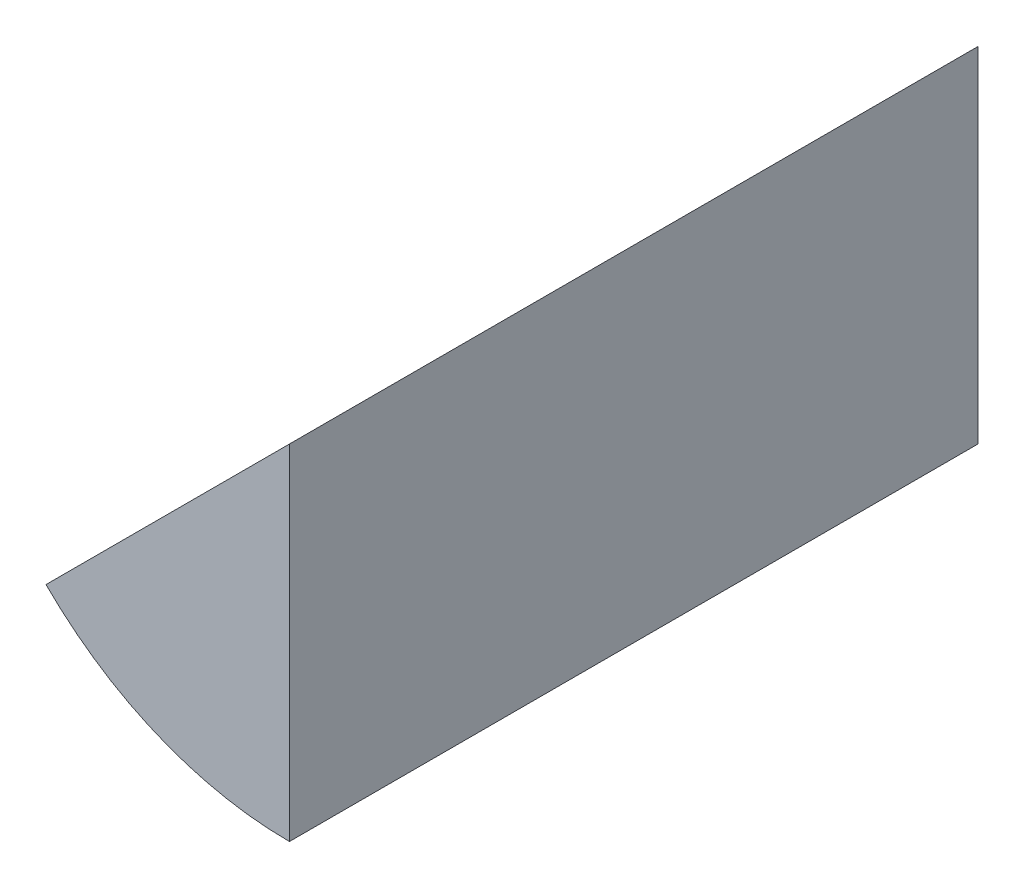
SolidWorks part; units mm, degrees
ref_plane "Alzado" through (0, 0, 0) normal (0, 0, 1) x (1, 0, 0)
ref_plane "Planta" through (0, 0, 0) normal (0, 1, 0) x (1, 0, 0)
ref_plane "Vista lateral" through (0, 0, 0) normal (1, 0, 0) x (0, 0, -1)
sketch "Croquis1" plane through (0, 0, 0) normal (0, 0, 1) x (1, 0, 0)
  line L0 (0, 0) -> (0, -25)
  line L2 (0, 0) -> (-17.6777, -17.6777)
  arc A0 (-17.6777, -17.6777) -> (0, -25) centre (0, 0) ccw
  dimension "D1" = 50
extrude "Saliente-Extruir1" add sketch "Croquis1" along normal blind 50
sketch "Croquis2" plane through (0, 0, 0) normal (0, 0, -1) x (-1, 0, 0)
  circle A0 centre (6.6972, -16.4372) radius 5
  dimension "D1" = 10
extrude "Cortar-Extruir1" cut sketch "Croquis2" against normal blind 10
